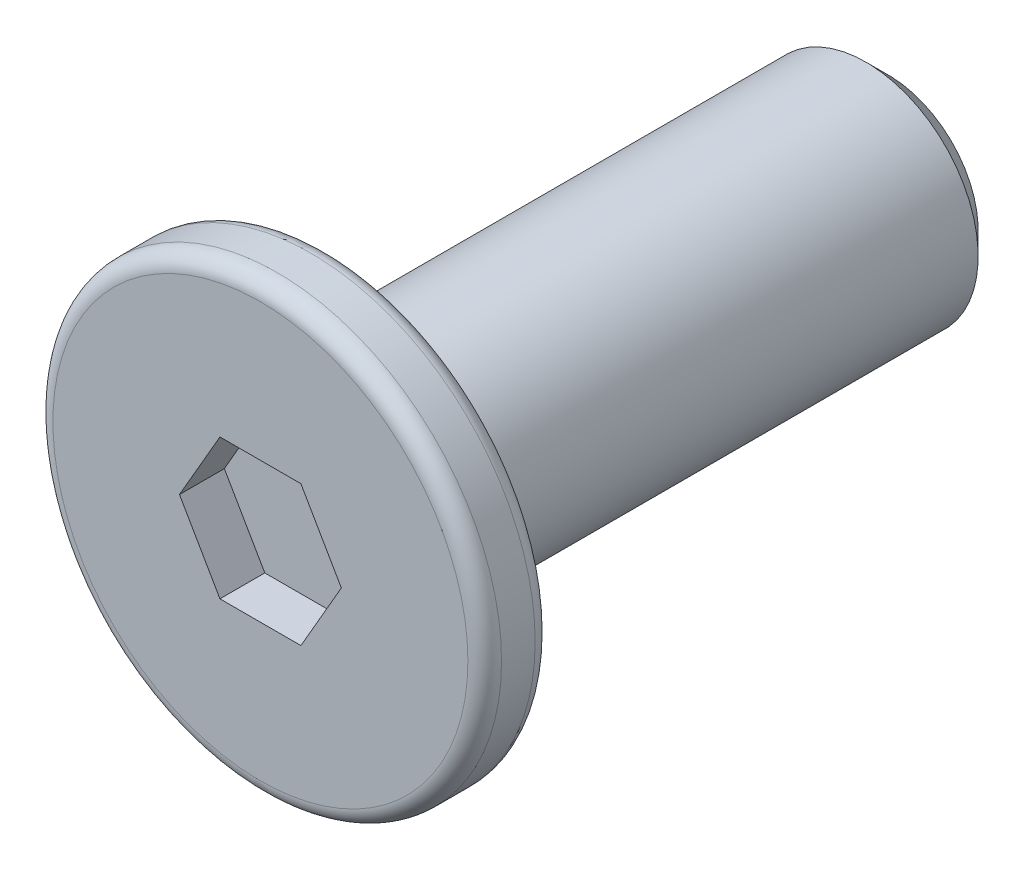
SolidWorks part; units mm, degrees
ref_plane "前视基准面" through (0, 0, 0) normal (0, 0, 1) x (1, 0, 0)
ref_plane "上视基准面" through (0, 0, 0) normal (0, 1, 0) x (1, 0, 0)
ref_plane "右视基准面" through (0, 0, 0) normal (1, 0, 0) x (0, 0, -1)
sketch "草图1" plane through (0, 0, 0) normal (0, 0, 1) x (1, 0, 0)
  circle A0 centre (0, 0) radius 4
  dimension "D1" = 8
extrude "凸台-拉伸1" add sketch "草图1" along normal mid plane 1.2
sketch "草图2" plane through (0, 0, -0.6) normal (0, 0, -1) x (-1, 0, 0)
  circle A0 centre (0, 0) radius 2
  dimension "D1" = 4
extrude "凸台-拉伸2" add sketch "草图2" along normal blind 10
chamfer "倒角1" distance 0.4 angle 45 1 edges at (-2, 0, -10.6)
sketch "草图3" plane through (0, 0, 0.6) normal (0, 0, 1) x (1, 0, 0)
  line L1 (1.4434, 0) -> (0.7217, 1.25)
  line L2 (0.7217, 1.25) -> (-0.7217, 1.25)
  line L3 (-0.7217, 1.25) -> (-1.4434, 0)
  line L4 (-1.4434, 0) -> (-0.7217, -1.25)
  line L5 (-0.7217, -1.25) -> (0.7217, -1.25)
  line L6 (0.7217, -1.25) -> (1.4434, 0)
  circle A0 centre (0, 0) radius 1.25 construction
  dimension "D1" = 2.5
extrude "切除-拉伸1" cut sketch "草图3" against normal blind 0.8
fillet "圆角2" radius 0.3 2 edges at (4, 0, -0.6) (4, 0, 0.6)
